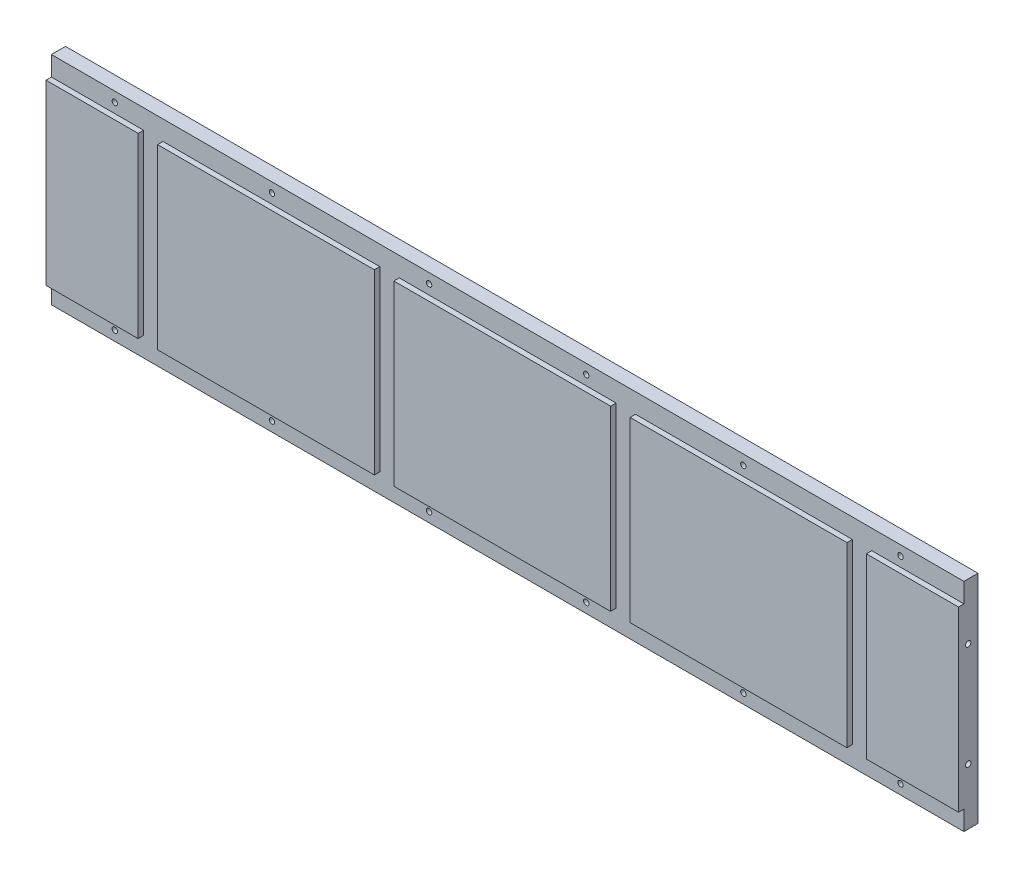
SolidWorks part; units mm, degrees
ref_plane "Front Plane" through (0, 0, 0) normal (0, 0, 1) x (1, 0, 0)
ref_plane "Top Plane" through (0, 0, 0) normal (0, 1, 0) x (1, 0, 0)
ref_plane "Right Plane" through (0, 0, 0) normal (1, 0, 0) x (0, 0, -1)
sketch "Sketch1" plane through (0, 0, 0) normal (0, 0, 1) x (1, 0, 0)
  line L1 (-421, 100) -> (421, 100)
  line L2 (-421, 100) -> (-421, -100)
  line L3 (-421, -100) -> (421, -100)
  line L4 (421, 100) -> (421, -100)
  line L5 (-421, 100) -> (421, -100) construction
  line L6 (-421, -100) -> (421, 100) construction
  point P0 (0, 0)
  dimension "D1" = 842
  dimension "D2" = 200
extrude "Boss-Extrude1" add sketch "Sketch1" along normal blind 18
sketch "Sketch2" plane through (421, 0, 0) normal (1, 0, 0) x (0, 0, -1)
  line L1 (-18, 100) -> (-13, 100)
  line L2 (-18, 100) -> (-18, 82)
  line L3 (-18, 82) -> (-13, 82)
  line L4 (-13, 100) -> (-13, 82)
  line L5 (-18, -100) -> (-13, -100)
  line L6 (-18, -100) -> (-18, -82)
  line L7 (-18, -82) -> (-13, -82)
  line L8 (-13, -100) -> (-13, -82)
  dimension "D1" = 18
  dimension "D2" = 5
  dimension "D3" = 18
  dimension "D4" = 5
extrude "Cut-Extrude1" cut sketch "Sketch2" against normal through all
sketch "Sketch3" plane through (0, 0, 18) normal (0, 0, 1) x (1, 0, 0)
  line L0 (-421, 82) -> (-421, -82) construction
  line L5 (-336, 134.6465) -> (-318, 134.6465)
  line L6 (-336, 134.6465) -> (-336, -160.234)
  line L7 (-336, -160.234) -> (-318, -160.234)
  line L8 (-318, 134.6465) -> (-318, -160.234)
  line L9 (-118, 134.6465) -> (-100, 134.6465)
  line L10 (-118, 134.6465) -> (-118, -160.234)
  line L11 (-118, -160.234) -> (-100, -160.234)
  line L12 (-100, 134.6465) -> (-100, -160.234)
  line L13 (100, 134.6465) -> (118, 134.6465)
  line L14 (100, 134.6465) -> (100, -160.234)
  line L15 (100, -160.234) -> (118, -160.234)
  line L16 (118, 134.6465) -> (118, -160.234)
  line L17 (318, 134.6465) -> (336, 134.6465)
  line L18 (318, 134.6465) -> (318, -160.234)
  line L19 (318, -160.234) -> (336, -160.234)
  line L20 (336, 134.6465) -> (336, -160.234)
  line L24 (421, -82) -> (421, 82) construction
  dimension "D2" = 18
  dimension "D3" = 18
  dimension "D4" = 18
  dimension "D5" = 18
  dimension "D6" = 85
  dimension "D7" = 200
  dimension "D8" = 200
  dimension "D9" = 200
  dimension "D11" = 85
extrude "Cut-Extrude2" cut sketch "Sketch3" against normal blind 5
hole_wizard "Ø5.0 (5) Diameter Hole1" positions "Sketch7" profile "Sketch6" hole size "Ø5.0" standard "ISO" end condition through all
sketch "Sketch7" plane through (0, 0, 13) normal (0, 0, 1) x (1, 0, 0)
  line L0 (-421, -100) -> (421, -100) construction
  line L1 (-421, 100) -> (421, 100) construction
  line L2 (421, 82) -> (421, 100) construction
  line L6 (-421, -100) -> (-421, -82) construction
  point P0 (-362.5, 91)
  point P2 (-217.5, 91)
  point P4 (-72.5, 91)
  point P6 (72.5, 91)
  point P8 (217.5, 91)
  point P10 (362.5, 91)
  point P12 (-362.5, -91)
  point P22 (217.5, -91)
  point P24 (362.5, -91)
  point P36 (-217.5, -91)
  point P38 (-72.5, -91)
  point P40 (72.5, -91)
  dimension "D1" = 9
  dimension "D2" = 9
  dimension "D3" = 9
  dimension "D4" = 9
  dimension "D5" = 9
  dimension "D6" = 9
  dimension "D7" = 9
  dimension "D8" = 9
  dimension "D9" = 9
  dimension "D10" = 9
  dimension "D11" = 9
  dimension "D12" = 9
  dimension "D13" = 145
  dimension "D14" = 145
  dimension "D15" = 145
  dimension "D16" = 145
  dimension "D17" = 145
  dimension "D18" = 58.5
  dimension "D19" = 58.5
  dimension "D20" = 145
  dimension "D21" = 145
  dimension "D22" = 145
  dimension "D23" = 145
  dimension "D24" = 145
sketch "Sketch6" plane through (-362.5, 91, 13) normal (1, 0, 0) x (0, -1, 0)
  line L0 (0, 0) -> (0, 13)
  line L1 (0, 13) -> (2.5, 13)
  line L2 (2.5, 13) -> (2.5, 0)
  line L5 (2.5, 0) -> (0, 0)
  line L11 (0, -6.35) -> (0, 107.95) construction
  dimension "Thru Hole Dia." = 5
  dimension "Thru Hole Depth" = 13
hole_wizard "Ø5.0 (5) Diameter Hole2" positions "Sketch9" profile "Sketch8" hole size "Ø5.0" standard "ISO"
sketch "Sketch9" plane through (421, 0, 0) normal (1, 0, 0) x (0, 0, -1)
  point P0 (-9, 48)
  point P3 (-9, -48)
sketch "Sketch8" plane through (421, 48, 9) normal (0, 1, 0) x (0, 0, -1)
  line L0 (0, 0) -> (0, 46.5022)
  line L1 (0, 46.5022) -> (2.5, 45)
  line L2 (2.5, 45) -> (2.5, 0)
  line L5 (2.5, 0) -> (0, 0)
  line L10 (0, 46.5022) -> (-2.5, 45) construction
  line L11 (0, -6.35) -> (0, 107.95) construction
  dimension "Hole Dia." = 5
  dimension "Hole Depth" = 45
  dimension "Drill Angle" = 118
hole_wizard "Ø5.0 (5) Diameter Hole3" positions "Sketch11" profile "Sketch10" hole size "Ø5.0" standard "ISO"
sketch "Sketch11" plane through (-421, 0, 0) normal (-1, 0, 0) x (0, 0, 1)
  point P0 (9, 48)
  point P3 (9, -48)
sketch "Sketch10" plane through (-421, 48, 9) normal (0, 1, 0) x (0, 0, 1)
  line L0 (0, 0) -> (0, 46.5022)
  line L1 (0, 46.5022) -> (2.5, 45)
  line L2 (2.5, 45) -> (2.5, 0)
  line L5 (2.5, 0) -> (0, 0)
  line L10 (0, 46.5022) -> (-2.5, 45) construction
  line L11 (0, -6.35) -> (0, 107.95) construction
  dimension "Hole Dia." = 5
  dimension "Hole Depth" = 45
  dimension "Drill Angle" = 118
